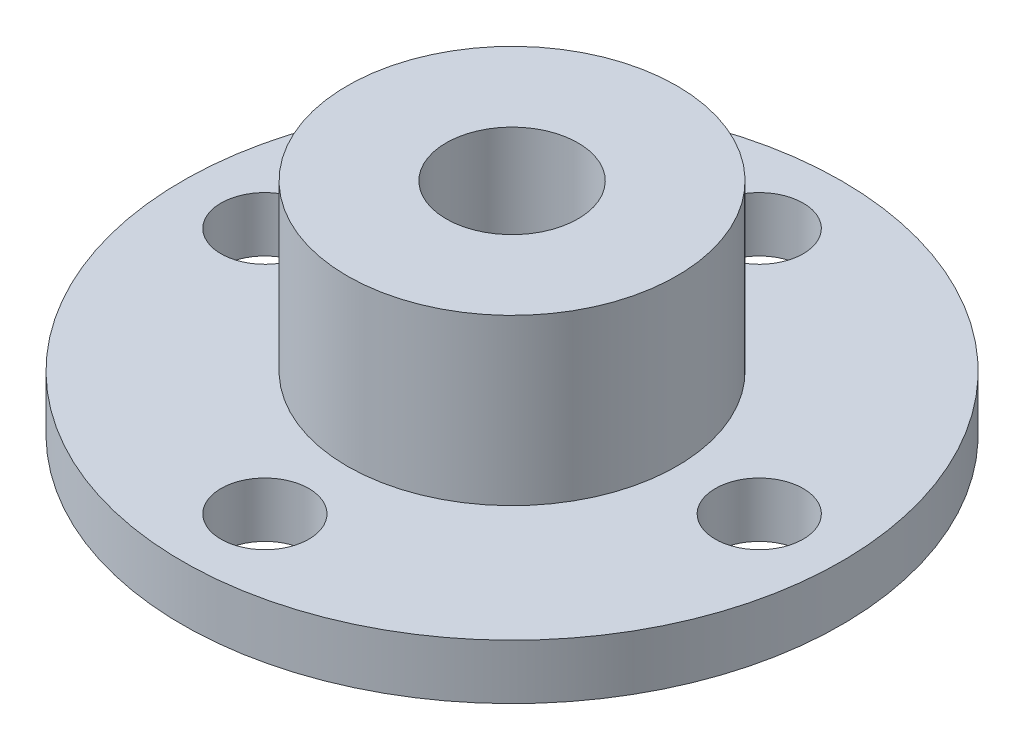
SolidWorks part; units mm, degrees
ref_plane "Front Plane" through (0, 0, 0) normal (0, 0, 1) x (1, 0, 0)
ref_plane "Top Plane" through (0, 0, 0) normal (0, 1, 0) x (1, 0, 0)
ref_plane "Right Plane" through (0, 0, 0) normal (1, 0, 0) x (0, 0, -1)
sketch "Sketch1" plane through (0, 0, 0) normal (0, 1, 0) x (1, 0, 0)
  circle A0 centre (0, 0) radius 3.81
  circle A1 centre (0, 0) radius 9.525
  dimension "D1" = 7.62
  dimension "D2" = 19.05
extrude "Boss-Extrude1" add sketch "Sketch1" along normal blind 12.7
sketch "Sketch2" plane through (0, 0, 0) normal (0, -1, 0) x (1, 0, 0)
  line L0 (0, 0) -> (0, 14.2875) construction
  line L1 (0, 9.525) -> (0, 19.05) construction
  line L2 (14.2875, 0) -> (0, 0) construction
  circle A0 centre (0, 0) radius 19.05
  circle A1 centre (0, 14.2875) radius 2.54
  circle A2 centre (0, 0) radius 9.525 construction
  circle A3 centre (0, 0) radius 9.525
  circle A4 centre (14.2875, 0) radius 2.54
  circle A5 centre (0, -14.2875) radius 2.54
  circle A6 centre (-14.2875, 0) radius 2.54
  point P8 (13.4329, 0)
  point P11 (0, 0)
  point P12 (0, 0)
  point P19 (0, 0)
  dimension "D1" = 38.1
  dimension "D2" = 5.08
  dimension "D3" = 4
extrude "Boss-Extrude2" add sketch "Sketch2" against normal blind 3.175
